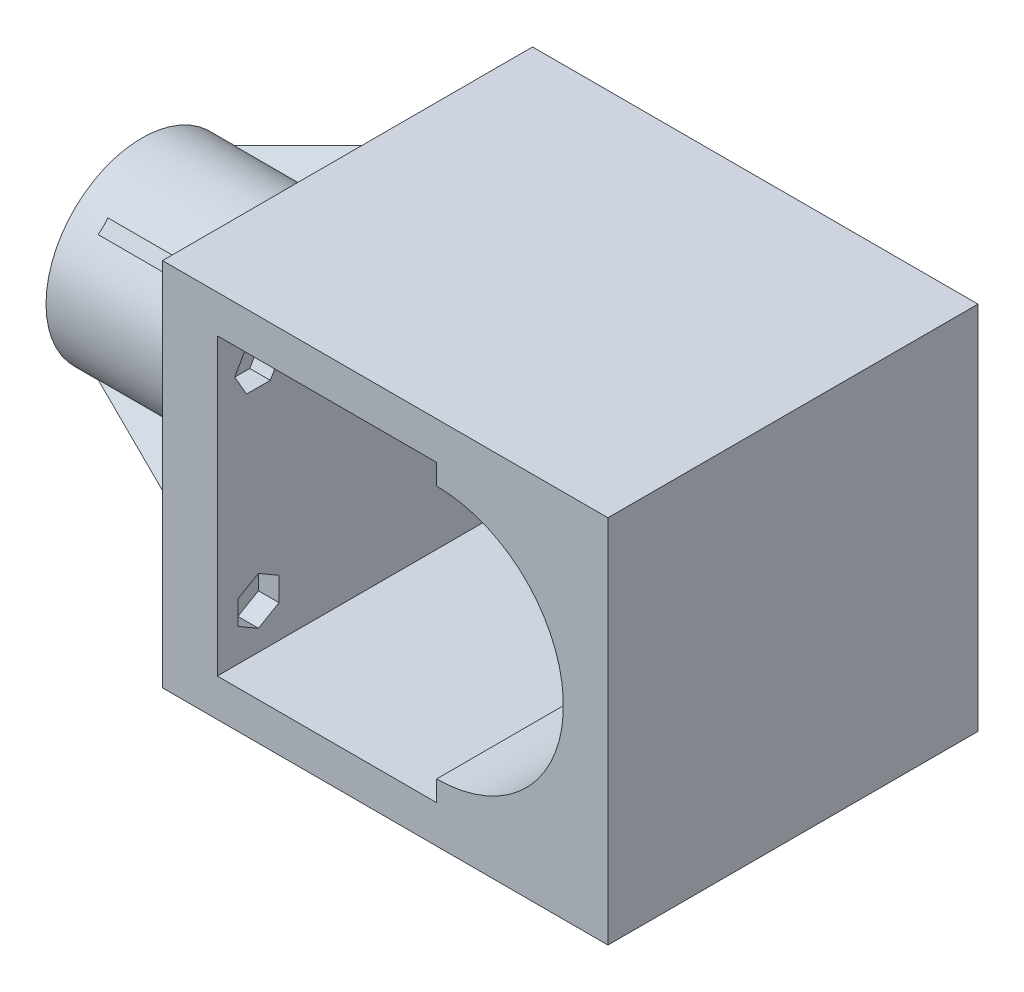
SolidWorks part; units mm, degrees
material "ABS PC"
ref_plane "Front Plane" through (0, 0, 0) normal (0, 0, 1) x (1, 0, 0)
ref_plane "Top Plane" through (0, 0, 0) normal (0, 1, 0) x (1, 0, 0)
ref_plane "Right Plane" through (0, 0, 0) normal (1, 0, 0) x (0, 0, -1)
sketch "Sketch1" plane through (0, 0, 0) normal (0, 1, 0) x (1, 0, 0)
  line L0 (32.5, -27) -> (32.5, 27)
  line L1 (-32.5, -27) -> (32.5, -27) construction
  line L2 (-32.5, -27) -> (-32.5, 27)
  line L3 (-32.5, 27) -> (32.5, 27)
  line L5 (-32.5, -27) -> (32.5, 27) construction
  line L6 (-32.5, 27) -> (32.5, -27) construction
  line L9 (-20, -27) -> (-32.5, -27)
  line L10 (-32.5, 0) -> (30, 0) construction
  line L11 (-20, -27) -> (32.5, -27)
  point P0 (0, 0)
  dimension "D1" = 65
  dimension "D2" = 54
ref_axis "Axis1" through (-32.5, 0, 0) along (1, 0, 0)
extrude "Boss-Extrude1" add sketch "Sketch1" along normal mid plane 54
sketch "Sketch2" plane through (-32.5, 0, 0) normal (-1, 0, 0) x (0, 0, 1)
  circle A0 centre (0, 0) radius 10
  dimension "D1" = 20
sketch "Sketch10" plane through (-32.5, 0, 0) normal (1, 0, 0) x (0, 0, -1)
  circle A0 centre (0, 0) radius 14
  dimension "D1" = 28
fillet "Fillet3" [suppressed] radius 3
extrude "Boss-Extrude5" add sketch "Sketch10" against normal blind 30
extrude "Cut-Extrude7" cut sketch "Sketch2" along normal up to surface (30 mm away) up to face at (-62.5, 0, -14)
ref_plane "Plane1" through (0, 0, 0) normal (0, 0.7071, -0.7071) x (-1, 0, 0)
sketch "Sketch16" plane through (0, 0, 0) normal (0, 0.7071, -0.7071) x (-1, 0, 0)
  line L0 (32.5, -14) -> (62.5, -14) construction
  line L1 (32.5, -38.1838) -> (32.5, 0) construction
  line L2 (32.5, -14) -> (62.5, -14) construction
  line L3 (32.5, -38.1838) -> (32.5, -14) construction
  line L4 (62.5, -14) -> (32.5, -38.1838) construction
  line L5 (62.5, -14) -> (62.5, 14) construction
  line L6 (62.5, -14) -> (62.5, 14) construction
  line L7 (62.5, 0) -> (19.7151, 0) construction
  line L8 (62.5, -12) -> (30, -12)
  line L9 (30, -12) -> (32.5, -26.0638)
  line L10 (32.5, -26.0638) -> (62.5, -12)
  line L11 (30, 12) -> (32.5, 26.0638)
  line L12 (62.5, 12) -> (30, 12)
  line L13 (32.5, 26.0638) -> (62.5, 12)
  dimension "D2" = 2
  dimension "D3" = 14.2843
extrude "Boss-Extrude9" add sketch "Sketch16" along normal mid plane 2
pattern_circular "CirPattern1" count 2 over 90 about axis through (0, 0, 0) along (1, 0, 0) of "Boss-Extrude9"
sketch "Sketch18" plane through (0, 0, 27) normal (0, 0, 1) x (1, 0, 0)
  line L0 (7.5, 0) -> (-2.5, 0) construction
  line L1 (7.5, -18.5) -> (-2.5, -18.5)
  line L2 (7.5, 18.5) -> (-2.5, 18.5)
  line L3 (-32.5, 27) -> (-32.5, -27) construction
  arc A0 (7.5, -18.5) -> (7.5, 18.5) centre (7.5, 0) ccw
  arc A1 (-2.5, 18.5) -> (-2.5, -18.5) centre (-2.5, 0) ccw
  point P3 (2.5, 0)
  dimension "D1" = 37
  dimension "D2" = 10
  dimension "D3" = 30
extrude "Cut-Extrude8" cut sketch "Sketch18" against normal blind 28
sketch "Sketch19" plane through (0, 0, -27) normal (0, 0, -1) x (-1, 0, 0)
  line L0 (2.5, 0) -> (-7.5, 0) construction
  line L1 (2.5, -17.5) -> (-7.5, -17.5)
  line L2 (2.5, 17.5) -> (-7.5, 17.5)
  line L3 (32.5, 27) -> (32.5, -27) construction
  arc A0 (2.5, -17.5) -> (2.5, 17.5) centre (2.5, 0) ccw
  arc A1 (-7.5, 17.5) -> (-7.5, -17.5) centre (-7.5, 0) ccw
  point P3 (-2.5, 0)
  dimension "D1" = 35
  dimension "D2" = 10
  dimension "D3" = 30
extrude "Cut-Extrude9" cut sketch "Sketch19" against normal blind 26
sketch "Sketch20" plane through (0, 0, 27) normal (0, 0, 1) x (1, 0, 0)
  line L2 (-24.5, 21.5) -> (-24.5, -21.5)
  line L3 (-24.5, -21.5) -> (7.5, -21.5)
  line L4 (7.5, -21.5) -> (7.5, -18.5)
  line L5 (-32.5, 27) -> (-32.5, -27) construction
  line L6 (7.5, -18.5) -> (7.5, 18.5)
  line L7 (-24.5, 21.5) -> (7.5, 21.5)
  line L10 (7.5, 18.5) -> (7.5, 21.5)
  arc A1 (7.5, -18.5) -> (7.5, 18.5) centre (7.5, 0) ccw construction
  arc A3 (7.5, -18.5) -> (7.5, 18.5) centre (7.5, 0) ccw construction
  dimension "D1" = 3
  dimension "D2" = 3
  dimension "D3" = 8
extrude "Cut-Extrude10" cut sketch "Sketch20" against normal through all
sketch "Sketch22" plane through (-24.5, 0, 0) normal (1, 0, 0) x (0, 0, -1)
  line L1 (-21, 15) -> (21, 15) construction
  line L2 (-21, 15) -> (-21, -15) construction
  line L3 (-21, -15) -> (21, -15) construction
  line L4 (21, 15) -> (21, -15) construction
  line L5 (-21, 15) -> (21, -15) construction
  line L6 (-21, -15) -> (21, 15) construction
  line L8 (27, 27) -> (27, -27) construction
  line L9 (18, -16.7321) -> (21, -18.4641)
  line L10 (21, -18.4641) -> (24, -16.7321)
  line L11 (24, -16.7321) -> (24, -13.2679)
  line L12 (24, -13.2679) -> (21, -11.5359)
  line L13 (21, -11.5359) -> (18, -13.2679)
  line L14 (18, -13.2679) -> (18, -16.7321)
  line L15 (-24, -16.7321) -> (-21, -18.4641)
  line L16 (-21, -18.4641) -> (-18, -16.7321)
  line L17 (-18, -16.7321) -> (-18, -13.2679)
  line L18 (-18, -13.2679) -> (-21, -11.5359)
  line L19 (-21, -11.5359) -> (-24, -13.2679)
  line L20 (-24, -13.2679) -> (-24, -16.7321)
  line L21 (-24.4641, 15) -> (-22.7321, 12)
  line L22 (-22.7321, 12) -> (-19.2679, 12)
  line L23 (-19.2679, 12) -> (-17.5359, 15)
  line L24 (-17.5359, 15) -> (-19.2679, 18)
  line L25 (-19.2679, 18) -> (-22.7321, 18)
  line L26 (-22.7321, 18) -> (-24.4641, 15)
  line L27 (18, 16.7321) -> (18, 13.2679)
  line L28 (18, 13.2679) -> (21, 11.5359)
  line L29 (21, 11.5359) -> (24, 13.2679)
  line L30 (24, 13.2679) -> (24, 16.7321)
  line L31 (24, 16.7321) -> (21, 18.4641)
  line L32 (21, 18.4641) -> (18, 16.7321)
  circle A0 centre (21, -15) radius 3 construction
  circle A1 centre (-21, -15) radius 3 construction
  circle A2 centre (-21, 15) radius 3 construction
  circle A3 centre (21, 15) radius 3 construction
  point P0 (0, 0)
  dimension "D3" = 6
  dimension "D4" = 6
  dimension "D5" = 6
  dimension "D6" = 6
  dimension "D1" = 6
  dimension "D2" = 30
extrude "Cut-Extrude11" cut sketch "Sketch22" against normal blind 3
equation "\"gimbalFrameLenght\"=65"
equation "\"D1@Sketch1\"=\"gimbalFrameLenght\""
equation "\"gimbalFrameHight\"=54"
equation "\"D2@Sketch1\"=\"gimbalFrameHight\""
equation "\"D1@Boss-Extrude1\"=\"gimbalFrameHight\""
